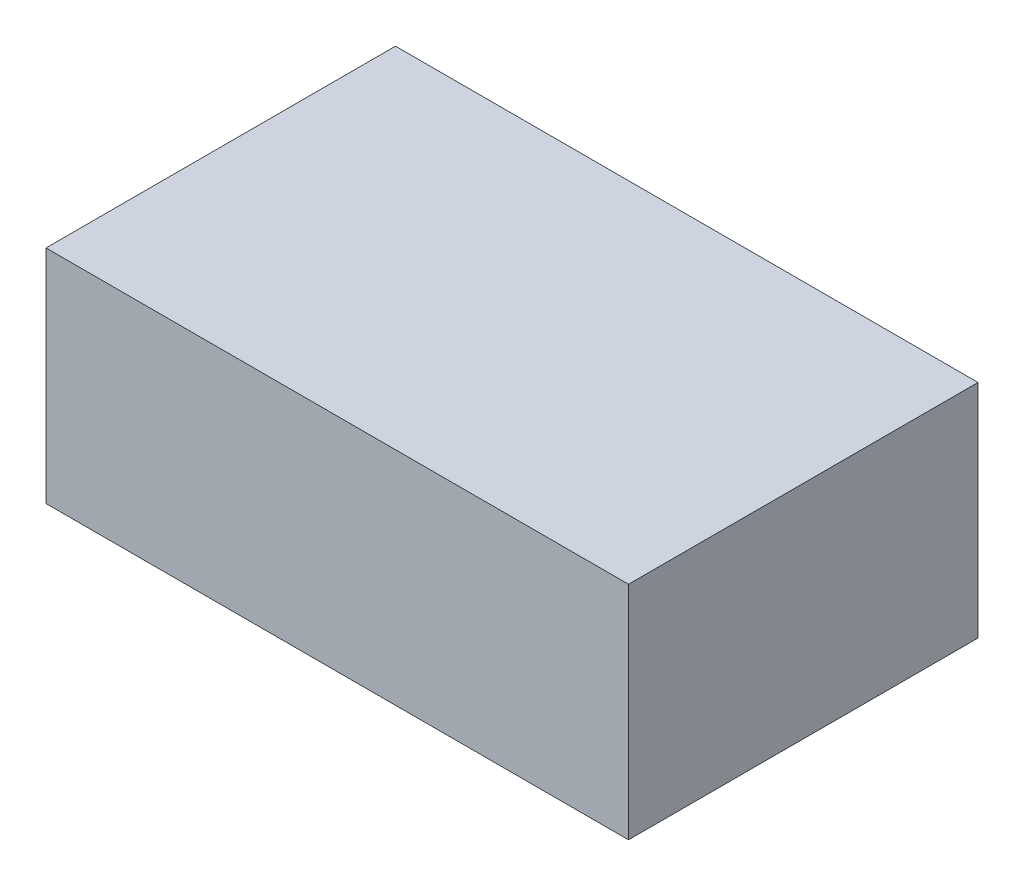
SolidWorks part; units mm, degrees
material "Melamine resin"
ref_plane "Front Plane" through (0, 0, 0) normal (0, 0, 1) x (1, 0, 0)
ref_plane "Top Plane" through (0, 0, 0) normal (0, 1, 0) x (1, 0, 0)
ref_plane "Right Plane" through (0, 0, 0) normal (1, 0, 0) x (0, 0, -1)
sketch "Sketch1" plane through (0, 0, 0) normal (0, 1, 0) x (1, 0, 0)
  line L1 (-25, -15) -> (25, -15)
  line L2 (-25, -15) -> (-25, 15)
  line L3 (-25, 15) -> (25, 15)
  line L4 (25, -15) -> (25, 15)
  line L5 (-25, -15) -> (25, 15) construction
  line L6 (-25, 15) -> (25, -15) construction
  point P0 (0, 0)
  dimension "D1" = 30
  dimension "D2" = 50
extrude "Boss-Extrude1" add sketch "Sketch1" along normal blind 19
